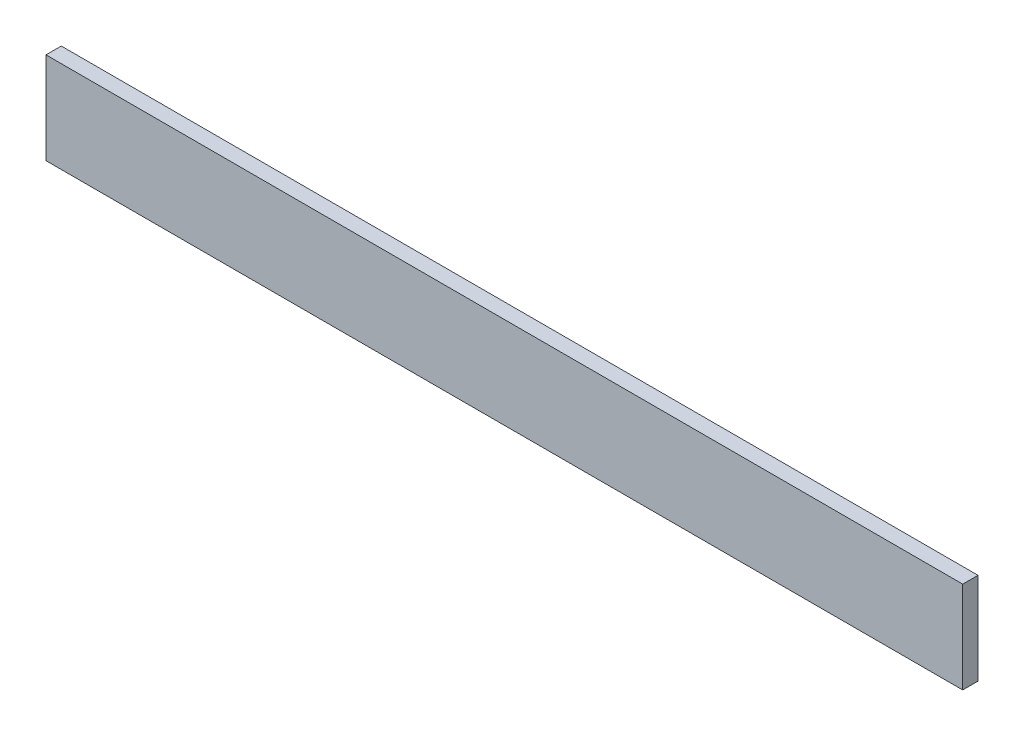
SolidWorks part; units mm, degrees
ref_plane "Plan de face" through (0, 0, 0) normal (0, 0, 1) x (1, 0, 0)
ref_plane "Plan de dessus" through (0, 0, 0) normal (0, 1, 0) x (1, 0, 0)
ref_plane "Plan de droite" through (0, 0, 0) normal (1, 0, 0) x (0, 0, -1)
sketch "Esquisse1" plane through (0, 0, 0) normal (0, 0, 1) x (1, 0, 0)
  line L1 (0, 0) -> (-300, 0)
  line L2 (0, 0) -> (0, -30)
  line L3 (0, -30) -> (-300, -30)
  line L4 (-300, 0) -> (-300, -30)
  dimension "D1" = 300
  dimension "D2" = 30
extrude "Boss.-Extru.1" add sketch "Esquisse1" along normal blind 5
